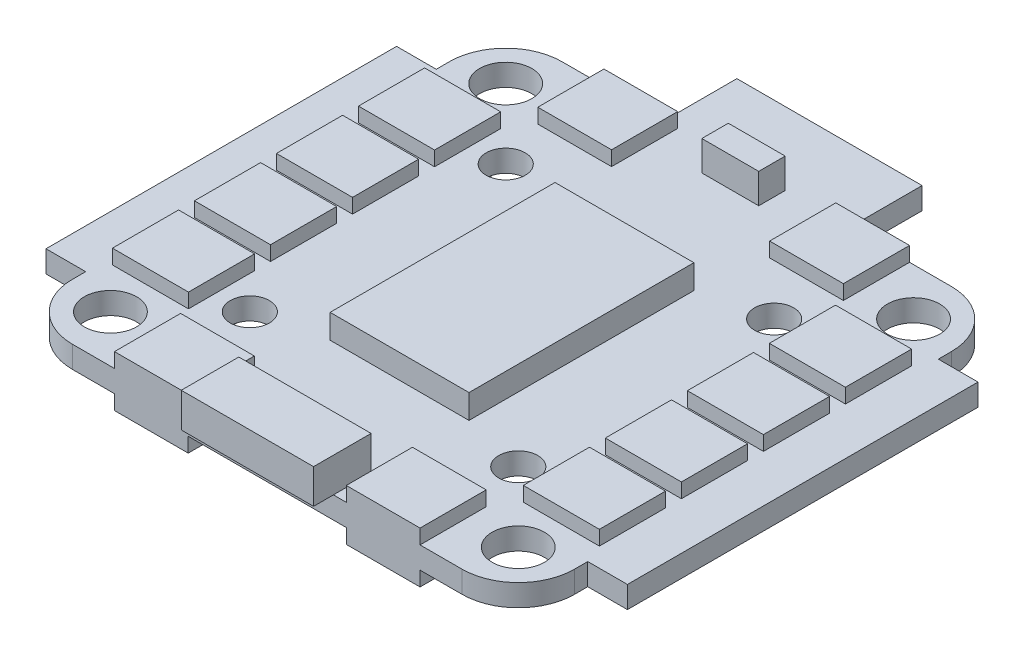
SolidWorks part; units mm, degrees
ref_plane "Front Plane" through (0, 0, 0) normal (0, 0, 1) x (1, 0, 0)
ref_plane "Top Plane" through (0, 0, 0) normal (0, 1, 0) x (1, 0, 0)
ref_plane "Right Plane" through (0, 0, 0) normal (1, 0, 0) x (0, 0, -1)
sketch "Sketch1" plane through (0, 0, 0) normal (0, 1, 0) x (1, 0, 0)
  line L0 (0, 0) -> (0, 86.5739) construction
  line L9 (-7, 42.5) -> (7, 42.5)
  line L10 (7, 42.5) -> (7, 37)
  line L11 (14.725, 37) -> (7, 37)
  line L13 (14.725, 0) -> (-14.725, 0)
  line L16 (-7, 42.5) -> (-7, 37)
  line L17 (18.975, 32.75) -> (18.975, 31.75)
  line L18 (21.975, 31.75) -> (21.975, 5.25)
  line L19 (18.975, 4.25) -> (18.975, 5.25)
  line L20 (15.4144, 33.4394) -> (17.7302, 35.7552) construction
  line L21 (17.7302, 35.7552) -> (16.811, 34.836) construction
  line L22 (21.975, 18.5) -> (10.1335, 18.5) construction
  line L23 (14.725, 37) -> (17.1885, 37) construction
  line L24 (18.975, 5.25) -> (21.975, 5.25)
  line L25 (18.975, 32.75) -> (18.975, 36.1901) construction
  line L26 (21.975, 31.75) -> (18.975, 31.75)
  line L27 (-18.975, 32.75) -> (-18.975, 31.75)
  line L28 (-21.975, 31.75) -> (-21.975, 5.25)
  line L29 (-18.975, 5.25) -> (-21.975, 5.25)
  line L30 (-18.975, 4.25) -> (-18.975, 5.25)
  line L31 (-21.975, 31.75) -> (-18.975, 31.75)
  line L32 (-14.725, 37) -> (-7, 37)
  arc A1 (18.975, 32.75) -> (14.725, 37) centre (14.725, 32.75) ccw
  arc A3 (14.725, 0) -> (18.975, 4.25) centre (14.725, 4.25) ccw
  circle A4 centre (15.4144, 33.4394) radius 1.975
  circle A5 centre (15.4144, 3.5606) radius 1.975
  arc A6 (-14.725, 0) -> (-18.975, 4.25) centre (-14.725, 4.25) cw
  circle A7 centre (-15.4144, 3.5606) radius 1.975
  circle A8 centre (-15.4144, 33.4394) radius 1.975
  arc A9 (-18.975, 32.75) -> (-14.725, 37) centre (-14.725, 32.75) cw
  point P15 (18.975, 31.75)
  point P23 (0, 42.5)
  point P24 (18.975, 33.2918)
  point P25 (18.975, 33.2092)
  point P26 (15.1773, 37)
  point P27 (0, 0)
  point P28 (15.4334, 33.1782)
  point P29 (15.3765, 33.4015)
  point P30 (14.9452, 37)
  point P50 (14.725, 4.25)
  dimension "D3" = 90
  dimension "D4" = 37
  dimension "D7" = 3
  dimension "D9" = 3.95
  dimension "D1" = 5.5
  dimension "D2" = 7
  dimension "D5" = 1.3
  dimension "D6" = 45
  dimension "D8" = 26.5
  dimension "D10" = 21.975
  dimension "D11" = 3
  dimension "D12" = 1
extrude "PCB" add sketch "Sketch1" along normal mid plane 1.65
sketch "Sketch7" plane through (0, 0.825, 0) normal (0, 1, 0) x (1, 0, 0)
  line L0 (21.975, 18.5) -> (-21.975, 18.5) construction
  line L1 (21.975, 5.25) -> (21.975, 31.75) construction
  line L2 (-21.975, 31.75) -> (-21.975, 5.25) construction
  line L3 (0, 42.5) -> (0, -1.4329) construction
  line L4 (7, 42.5) -> (-7, 42.5) construction
  line L5 (15.4144, 33.4394) -> (10.1465, 28.1715) construction
  line L6 (14.725, 37) -> (7, 37) construction
  line L7 (14.0179, 32.0429) -> (11.1895, 29.2145) construction
  circle A0 centre (10.1465, 28.1715) radius 1.475
  circle A1 centre (15.4144, 33.4394) radius 1.975 construction
  circle A2 centre (-10.1465, 28.1715) radius 1.475
  circle A3 centre (-10.1465, 8.8285) radius 1.475
  circle A4 centre (10.1465, 8.8285) radius 1.475
  point P11 (0, 0)
  point P22 (9.9228, 27.734)
  point P23 (0, 0)
  point P24 (9.9228, 27.9341)
  point P25 (0, 0)
  point P26 (10.1891, 28.2141)
  dimension "D3" = 2.95
  dimension "D1" = 45
  dimension "D2" = 4
extrude "inner holes" cut sketch "Sketch7" against normal through all both and the other way through all
sketch "Sketch8" plane through (0, 0.825, 0) normal (0, 1, 0) x (1, 0, 0)
  line L1 (-5, 2.85) -> (5, 2.85)
  line L2 (-5, 2.85) -> (-5, -1.5)
  line L3 (-5, -1.5) -> (5, -1.5)
  line L4 (5, 2.85) -> (5, -1.5)
  line L5 (-14.725, 0) -> (14.725, 0) construction
  point P4 (0, 2.85)
  dimension "D1" = 10
  dimension "D2" = 4.35
  dimension "D3" = 1.5
extrude "Connector" add sketch "Sketch8" along normal blind 2.6
sketch "Sketch9" plane through (0, 0.825, 0) normal (0, 1, 0) x (1, 0, 0)
  line L0 (-7, 37) -> (-14.725, 37) construction
  line L1 (-2.15, 37) -> (2.15, 37)
  line L2 (-2.15, 37) -> (-2.15, 35)
  line L3 (-2.15, 35) -> (2.15, 35)
  line L4 (2.15, 37) -> (2.15, 35)
  line L5 (0, 42.5) -> (0, 40.4487) construction
  line L6 (7, 42.5) -> (-7, 42.5) construction
  point P11 (0, 0)
  point P12 (0, 37)
  dimension "D1" = 4.3
  dimension "D2" = 2
extrude "Top component" add sketch "Sketch9" along normal blind 2.255
sketch "Sketch10" plane through (0, 0.825, 0) normal (0, 1, 0) x (1, 0, 0)
  line L0 (0, 42.5) -> (0, 11.1465) construction
  line L1 (7, 42.5) -> (-7, 42.5) construction
  line L2 (-21.975, 18.5) -> (21.975, 18.5) construction
  line L3 (-21.975, 31.75) -> (-21.975, 5.25) construction
  line L4 (21.975, 5.25) -> (21.975, 31.75) construction
  line L5 (12.655, 17.9) -> (18.405, 17.9)
  line L6 (12.655, 11.7) -> (18.405, 11.7)
  line L7 (12.655, 11.7) -> (12.655, 6.7)
  line L8 (12.655, 6.7) -> (18.405, 6.7)
  line L9 (18.405, 11.7) -> (18.405, 6.7)
  line L10 (12.655, 17.9) -> (12.655, 12.9)
  line L11 (12.655, 12.9) -> (18.405, 12.9)
  line L12 (18.405, 17.9) -> (18.405, 12.9)
  line L13 (12.655, 24.1) -> (18.405, 24.1)
  line L14 (12.655, 24.1) -> (12.655, 19.1)
  line L15 (12.655, 19.1) -> (18.405, 19.1)
  line L16 (18.405, 24.1) -> (18.405, 19.1)
  line L17 (12.655, 30.3) -> (18.405, 30.3)
  line L18 (12.655, 30.3) -> (12.655, 25.3)
  line L19 (12.655, 25.3) -> (18.405, 25.3)
  line L20 (18.405, 30.3) -> (18.405, 25.3)
  line L21 (5, 0) -> (14.725, 0) construction
  line L24 (-12.655, 6.7) -> (-18.405, 6.7)
  line L25 (-18.405, 11.7) -> (-18.405, 6.7)
  line L26 (-12.655, 11.7) -> (-18.405, 11.7)
  line L27 (-12.655, 11.7) -> (-12.655, 6.7)
  line L28 (-12.655, 17.9) -> (-12.655, 12.9)
  line L29 (-12.655, 12.9) -> (-18.405, 12.9)
  line L30 (-18.405, 17.9) -> (-18.405, 12.9)
  line L31 (-12.655, 17.9) -> (-18.405, 17.9)
  line L32 (-12.655, 24.1) -> (-12.655, 19.1)
  line L33 (-12.655, 19.1) -> (-18.405, 19.1)
  line L34 (-18.405, 24.1) -> (-18.405, 19.1)
  line L35 (-12.655, 24.1) -> (-18.405, 24.1)
  line L36 (-12.655, 30.3) -> (-12.655, 25.3)
  line L37 (-12.655, 25.3) -> (-18.405, 25.3)
  line L38 (-18.405, 30.3) -> (-18.405, 25.3)
  line L39 (-12.655, 30.3) -> (-18.405, 30.3)
  dimension "D1" = 5.75
  dimension "D2" = 5
  dimension "D3" = 1.2
  dimension "D4" = 1.2
  dimension "D5" = 1.2
  dimension "D6" = 3.57
  dimension "D7" = 11.7
extrude "Side Components" add sketch "Sketch10" along normal blind 1.1
sketch "Sketch11" plane through (0, 0.825, 0) normal (0, 1, 0) x (1, 0, 0)
  line L0 (0, 42.5) -> (0, 40.6485) construction
  line L1 (-5.25, 27) -> (5.25, 27)
  line L2 (-5.25, 27) -> (-5.25, 10)
  line L3 (-5.25, 10) -> (5.25, 10)
  line L4 (5.25, 27) -> (5.25, 10)
  line L5 (7, 42.5) -> (-7, 42.5) construction
  line L6 (-21.975, 31.75) -> (-21.975, 5.25) construction
  point P9 (0, 27)
  point P12 (-21.975, 18.5)
  point P13 (-5.25, 18.5)
  dimension "D1" = 10.5
  dimension "D2" = 17
extrude "Central components" add sketch "Sketch11" along normal blind 1.825
sketch "Sketch12" plane through (0, 0.825, 0) normal (0, 1, 0) x (1, 0, 0)
  line L0 (0, 42.5) -> (0, 31.1097) construction
  line L1 (7, 42.5) -> (-7, 42.5) construction
  line L2 (-21.975, 18.5) -> (21.975, 18.5) construction
  line L3 (-21.975, 31.75) -> (-21.975, 5.25) construction
  line L4 (21.975, 5.25) -> (21.975, 31.75) construction
  line L5 (14.725, 37) -> (7, 37) construction
  line L6 (5.975, 37) -> (11.55, 37)
  line L7 (5.975, 37) -> (5.975, 32)
  line L8 (5.975, 32) -> (11.55, 32)
  line L9 (11.55, 37) -> (11.55, 32)
  line L10 (5.975, 5) -> (11.55, 5)
  line L11 (11.55, 0) -> (11.55, 5)
  line L12 (5.975, 0) -> (11.55, 0)
  line L13 (5.975, 0) -> (5.975, 5)
  line L14 (-5.975, 0) -> (-5.975, 5)
  line L15 (-5.975, 0) -> (-11.55, 0)
  line L16 (-11.55, 0) -> (-11.55, 5)
  line L17 (-5.975, 5) -> (-11.55, 5)
  line L18 (-5.975, 32) -> (-11.55, 32)
  line L19 (-11.55, 37) -> (-11.55, 32)
  line L20 (-5.975, 37) -> (-11.55, 37)
  line L21 (-5.975, 37) -> (-5.975, 32)
  dimension "D1" = 5.575
  dimension "D2" = 16
  dimension "D3" = 5
extrude "Top and bottom components" add sketch "Sketch12" along normal blind 1.105
mirror "Mirror2" about plane through (0, 0, 0) normal (0, 1, 0) of "Side Components", "Top and bottom components"
